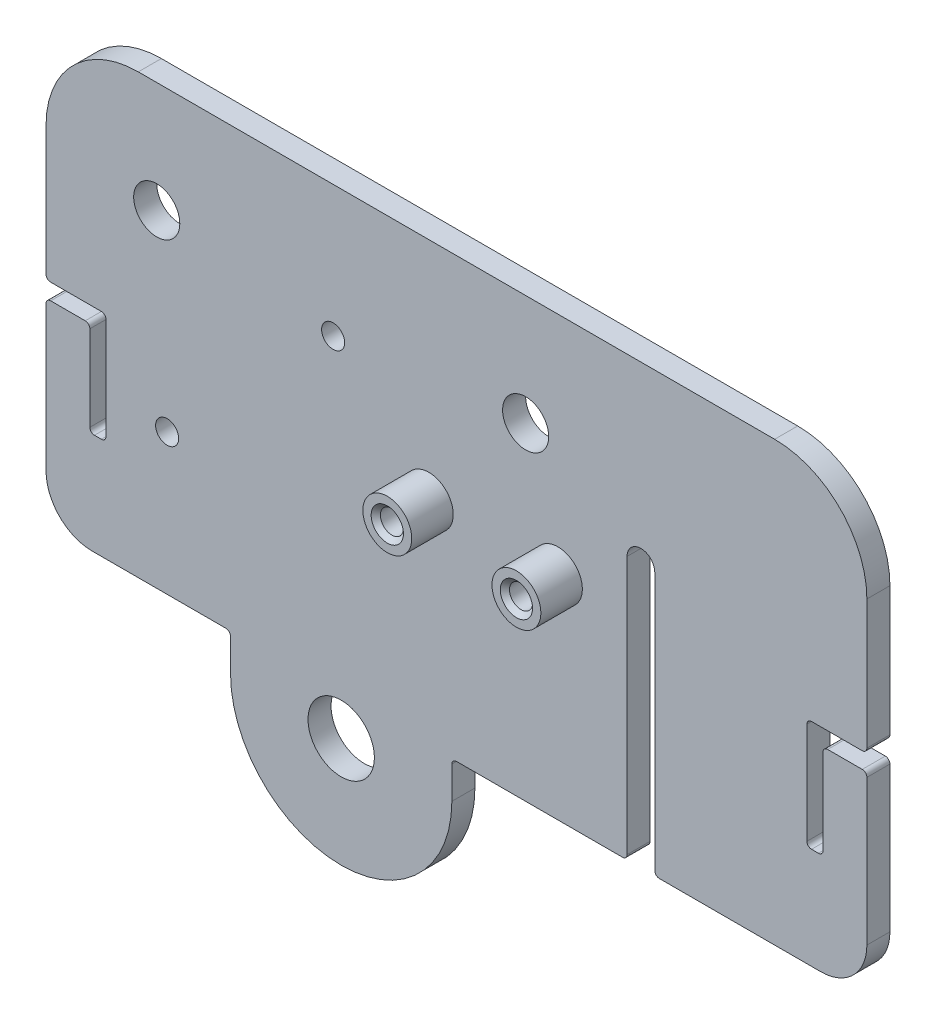
SolidWorks part; units mm, degrees
ref_plane "Front Plane" through (0, 0, 0) normal (0, 0, 1) x (1, 0, 0)
ref_plane "Top Plane" through (0, 0, 0) normal (0, 1, 0) x (1, 0, 0)
ref_plane "Right Plane" through (0, 0, 0) normal (1, 0, 0) x (0, 0, -1)
sketch "Sketch1" plane through (0, 0, 0) normal (0, 0, 1) x (1, 0, 0)
  line L0 (-0.5, -27.75) -> (-0.5, -23.75)
  line L1 (44.5, -23.75) -> (-0.5, -23.75)
  line L2 (44.5, -23.75) -> (44.5, 23.75)
  line L3 (44.5, 23.75) -> (-44.5, 23.75)
  line L4 (-44.5, -23.75) -> (-44.5, 23.75)
  line L5 (44.5, -23.75) -> (-44.5, 23.75) construction
  line L6 (44.5, 23.75) -> (-44.5, -23.75) construction
  line L7 (-24.5, -27.75) -> (-24.5, -23.75)
  line L8 (-24.5, -23.75) -> (-44.5, -23.75)
  line L9 (-12.5, -27.75) -> (-12.5, -27.85) construction
  line L10 (7.5, 11.75) -> (-32.5, 11.75) construction
  arc A0 (-24.5, -27.75) -> (-0.5, -27.75) centre (-12.5, -27.75) ccw
  circle A1 centre (-12.5, -27.85) radius 3.6
  circle A2 centre (7.5, 11.75) radius 2.5
  circle A3 centre (-32.5, 11.75) radius 2.5
  point P0 (0, 0)
  dimension "D3" = 24
  dimension "D4" = 16
  dimension "D6" = 7.2
  dimension "D7" = 8.3
  dimension "D9" = 5
  dimension "D1" = 47.5
  dimension "D2" = 89
  dimension "D5" = 20
  dimension "D8" = 40
  dimension "D10" = 12
  dimension "D11" = 12
extrude "Boss-Extrude1" add sketch "Sketch1" along normal mid plane 2.5
fillet "Fillet1" radius 5 2 edges at (44.5, -23.75, 0) (-44.5, -23.75, 0)
fillet "Fillet2" radius 10 2 edges at (44.5, 23.75, 0) (-44.5, 23.75, 0)
sketch "Sketch2" plane through (0, 0, 1.25) normal (0, 0, 1) x (1, 0, 0)
  line L8 (0, 0) -> (0, 23.75) construction
  line L9 (34.5, 23.75) -> (-34.5, 23.75) construction
  line L16 (-0.5, -23.75) -> (39.5, -23.75) construction
  line L17 (18.5, -23.75) -> (21.5, -23.75)
  line L18 (18.5, -23.75) -> (18.5, 4.75)
  line L19 (20, 3.25) -> (21.5, 3.25) construction
  line L20 (21.5, -23.75) -> (21.5, 4.75)
  line L22 (18.5, 4.75) -> (18.5, 3.25) construction
  line L23 (18.5, 3.25) -> (20, 3.25) construction
  line L24 (21.5, 4.75) -> (21.5, 3.25) construction
  line L31 (44.5, -18.75) -> (44.5, 13.75) construction
  line L32 (44.5, -0.75) -> (38, -0.75)
  line L33 (38, -0.75) -> (38, -12.75)
  line L34 (38, -12.75) -> (39.75, -12.75)
  line L35 (39.75, -12.75) -> (39.75, -2.5)
  line L36 (39.75, -2.5) -> (44.5, -2.5)
  line L37 (44.5, -2.5) -> (44.5, -0.75)
  line L38 (-0.5, -23.75) -> (39.5, -23.75) construction
  line L39 (-38, -12.75) -> (-39.75, -12.75)
  line L40 (-39.75, -12.75) -> (-39.75, -2.5)
  line L41 (-39.75, -2.5) -> (-44.5, -2.5)
  line L42 (-44.5, -2.5) -> (-44.5, -0.75)
  line L43 (-44.5, -0.75) -> (-38, -0.75)
  line L44 (-38, -0.75) -> (-38, -12.75)
  arc A8 (18.5, 4.75) -> (21.5, 4.75) centre (20, 4.75) ccw construction
  arc A9 (21.5, 4.75) -> (18.5, 4.75) centre (20, 4.75) ccw
  dimension "D5" = 12
  dimension "D6" = 11
  dimension "D1" = 23
  dimension "D2" = 6.5
  dimension "D3" = 1.75
  dimension "D4" = 1.75
  dimension "D8" = 3
  dimension "D9" = 30
extrude "Cut-Extrude1" cut sketch "Sketch2" against normal through all
fillet "Fillet3" radius 0.5 16 edges at (21.5, -23.75, 0) (18.5, -23.75, 0) (39.75, -12.75, 0) (38, -12.75, 0) (38, -0.75, 0) (-44.5, -0.75, 0) (-38, -0.75, 0) (-38, -12.75, 0) (-39.75, -12.75, 0) (-39.75, -2.5, 0) (-44.5, -2.5, 0) (-24.5, -23.75, 0) (-0.5, -23.75, 0) (44.5, -2.5, 0) (39.75, -2.5, 0) (44.5, -0.75, 0)
sketch "Sketch3" plane through (0, 0, 1.25) normal (0, 0, 1) x (1, 0, 0)
  line L0 (-3, -0.75) -> (11, -0.75) construction
  line L1 (0, -23.75) -> (18, -23.75) construction
  line L3 (18.5, 4.75) -> (18.5, -23.25) construction
  circle A0 centre (11, -0.75) radius 2.65
  circle A1 centre (-3, -0.75) radius 2.65
  dimension "D1" = 5.3
  dimension "D2" = 14
  dimension "D3" = 23
  dimension "D4" = 7.5
extrude "Boss-Extrude2" add sketch "Sketch3" along normal blind 4.5
hole_wizard "M3x0.5 Tapped Hole1" positions "Sketch5" profile "Sketch6" tap size "M3x0.5" standard "ANSI Metric"
sketch "Sketch5" plane through (0, 0, 5.75) normal (0, 0, 1) x (1, 0, 0)
  point P0 (-3, -0.75)
  point P3 (11, -0.75)
sketch "Sketch6" plane through (-3, -0.75, 5.75) normal (1, 0, 0) x (0, -1, 0)
  line L0 (0, 0) -> (0, 6.7511)
  line L1 (0, 6.7511) -> (1.25, 6)
  line L2 (1.25, 6) -> (1.25, 0.5)
  line L3 (1.25, 0.5) -> (1.75, 0)
  line L5 (1.75, 0) -> (0, 0)
  line L6 (-1.25, 0.5) -> (-1.75, 0) construction
  line L10 (0, 6.7511) -> (-1.25, 6) construction
  line L11 (0, -6.35) -> (0, 107.95) construction
  dimension "Tap Drill Dia." = 2.5
  dimension "Tap Drill Depth" = 6
  dimension "Near C'Sink Dia." = 3.5
  dimension "Near C'Sink Angle" = 90
  dimension "Drill Angle" = 118
cosmetic thread "Hole Thread1" parameters "D1"=6, "D2"=3
cosmetic thread "Hole Thread2" parameters "D1"=6, "D2"=3
sketch "Sketch7" plane through (0, 0, -1.25) normal (0, 0, -1) x (-1, 0, 0)
  line L2 (44.5, -3) -> (44.5, -18.75) construction
  line L3 (-34.5, 23.75) -> (34.5, 23.75) construction
  circle A0 centre (13.375, 9.5) radius 2.625
  circle A1 centre (31.375, -8.5) radius 2.625
  dimension "D1" = 5.25
  dimension "D2" = 18
  dimension "D3" = 11.625
  dimension "D4" = 18
  dimension "D5" = 10.5
extrude "Boss-Extrude3" add sketch "Sketch7" along normal blind 1.5
hole_wizard "M3x0.5 Tapped Hole2" positions "Sketch8" profile "Sketch9" tap size "M3x0.5" standard "ANSI Metric" end condition through all
sketch "Sketch8" plane through (0, 0, -2.75) normal (0, 0, -1) x (-1, 0, 0)
  point P0 (13.375, 9.5)
  point P3 (31.375, -8.5)
sketch "Sketch9" plane through (-13.375, 9.5, -2.75) normal (1, 0, 0) x (0, 1, 0)
  line L0 (0, 0) -> (0, 8.5)
  line L1 (0, 8.5) -> (1.25, 8.5)
  line L2 (1.25, 8.5) -> (1.25, 0.5)
  line L3 (1.25, 0.5) -> (1.75, 0)
  line L5 (1.75, 0) -> (0, 0)
  line L6 (-1.25, 0.5) -> (-1.75, 0) construction
  line L11 (0, -6.35) -> (0, 107.95) construction
  dimension "Thru Tap Drill Dia." = 2.5
  dimension "Thru Tap Drill Depth" = 8.5
  dimension "Near C'Sink Dia." = 3.5
  dimension "Near C'Sink Angle" = 90
cosmetic thread "Hole Thread3" parameters "D2"=3
cosmetic thread "Hole Thread4" parameters "D2"=3
